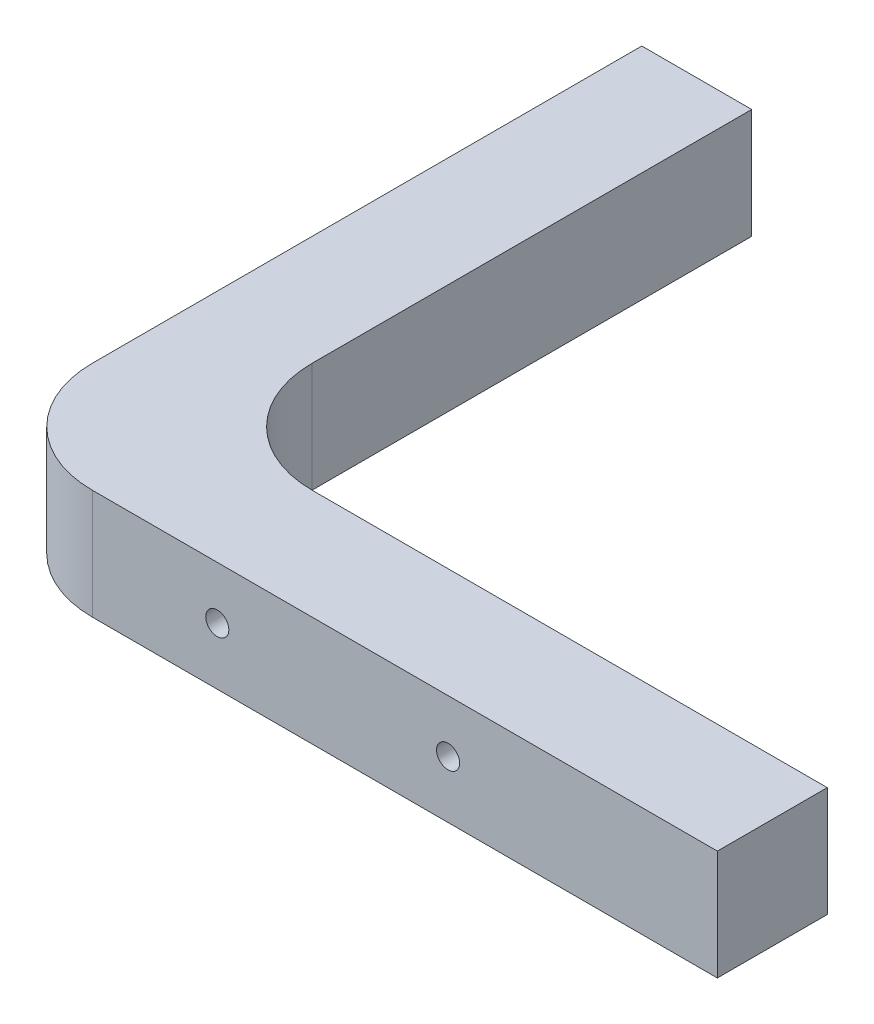
SolidWorks part; units mm, degrees
material "PTFE (general)"
ref_plane "Front Plane" through (0, 0, 0) normal (0, 0, 1) x (1, 0, 0)
ref_plane "Top Plane" through (0, 0, 0) normal (0, 1, 0) x (1, 0, 0)
ref_plane "Right Plane" through (0, 0, 0) normal (1, 0, 0) x (0, 0, -1)
sketch "Sketch1" plane through (0, 0, 0) normal (0, 1, 0) x (1, 0, 0)
  line L0 (23.1763, 46.7218) -> (-90.5737, 46.7218)
  line L1 (-110.5737, 66.7218) -> (-110.5737, 166.7218)
  line L2 (-110.5737, 166.7218) -> (-90.5737, 166.7218)
  line L3 (-90.5737, 166.7218) -> (-90.5737, 86.7218)
  line L4 (-70.5737, 66.7218) -> (23.1763, 66.7218)
  line L5 (23.1763, 66.7218) -> (23.1763, 46.7218)
  arc A0 (-90.5737, 46.7218) -> (-110.5737, 66.7218) centre (-90.5737, 66.7218) cw
  arc A1 (-90.5737, 86.7218) -> (-70.5737, 66.7218) centre (-70.5737, 86.7218) ccw
  point P8 (-110.5737, 46.7218)
  point P11 (-90.5737, 66.7218)
  dimension "D5" = 20
  dimension "D1" = 20
  dimension "D2" = 20
  dimension "D3" = 113.75
  dimension "D4" = 120
extrude "Boss-Extrude1" add sketch "Sketch1" along normal blind 20
sketch "Sketch2" plane through (0, 0, -66.7218) normal (0, 0, -1) x (-1, 0, 0)
  line L0 (-23.1763, 10.3977) -> (70.5737, 10.3977) construction
  line L1 (-23.1763, 20) -> (-23.1763, 0) construction
  line L2 (70.5737, 20) -> (70.5737, 0) construction
  line L3 (46.8237, 20) -> (46.8237, 0) construction
  line L5 (-23.1763, 0) -> (70.5737, 0) construction
  line L6 (-23.1763, 20) -> (70.5737, 20) construction
  circle A0 centre (25.8237, 10.3977) radius 2.1
  circle A2 centre (67.8237, 10.3977) radius 2.1
  dimension "D1" = 4.2
  dimension "D2" = 70
  dimension "D3" = 21
extrude "Cut-Extrude3" cut sketch "Sketch2" against normal up to surface (20 mm away) up to face at (-33.6987, 10, -46.7218)
